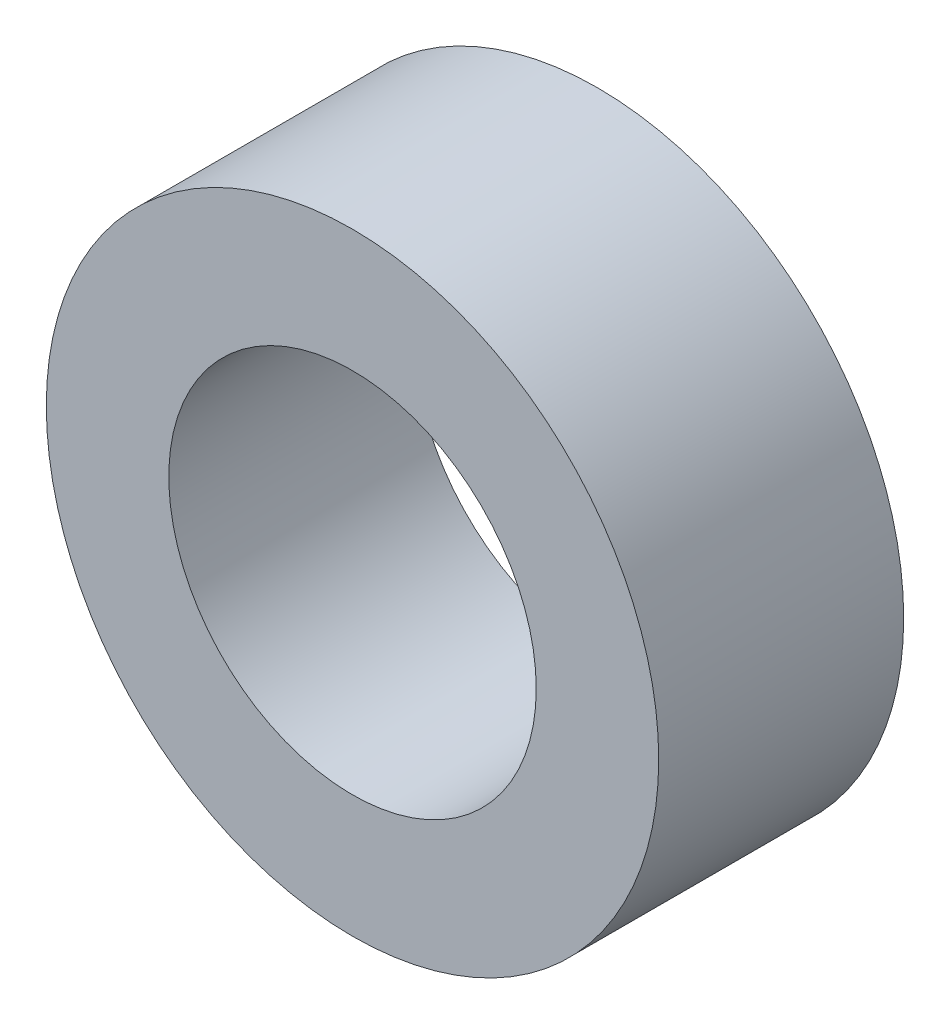
SolidWorks part; units mm, degrees
ref_plane "Front Plane" through (0, 0, 0) normal (0, 0, 1) x (1, 0, 0)
ref_plane "Top Plane" through (0, 0, 0) normal (0, 1, 0) x (1, 0, 0)
ref_plane "Right Plane" through (0, 0, 0) normal (1, 0, 0) x (0, 0, -1)
sketch "Sketch1" plane through (0, 0, 0) normal (0, 0, 1) x (1, 0, 0)
  circle A0 centre (0, 0) radius 2.3813
  circle A1 centre (0, 0) radius 3.9688
  dimension "D1" = 4.7625
  dimension "D2" = 7.9375
extrude "Boss-Extrude1" add sketch "Sketch1" along normal blind 3.175
